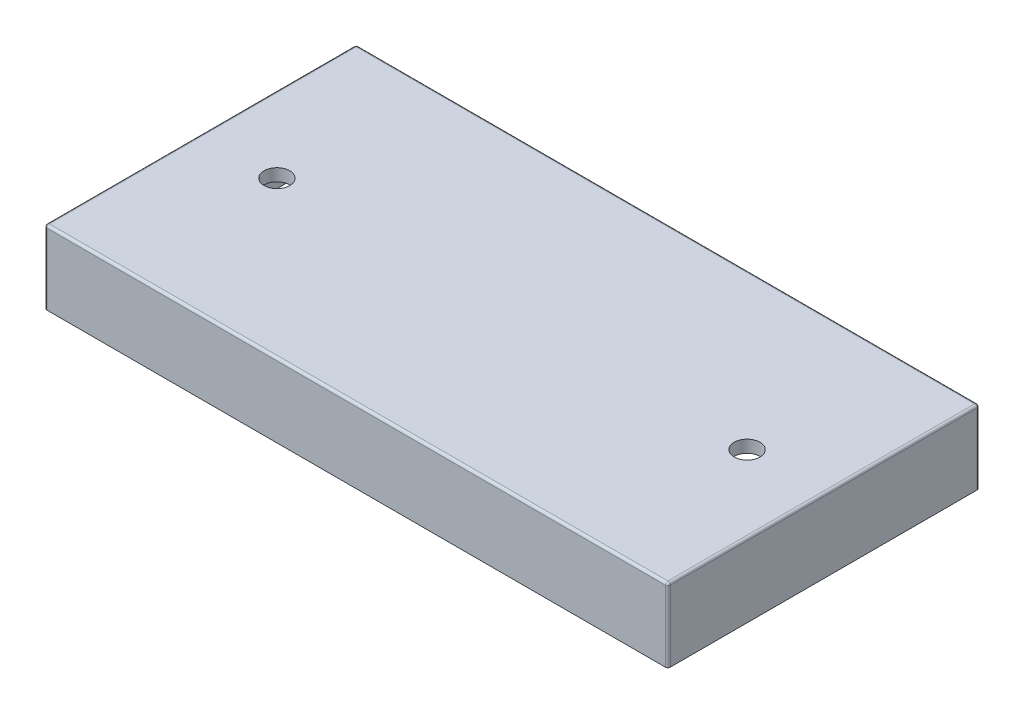
SolidWorks part; units mm, degrees
ref_plane "Front Plane" through (0, 0, 0) normal (0, 0, 1) x (1, 0, 0)
ref_plane "Top Plane" through (0, 0, 0) normal (0, 1, 0) x (1, 0, 0)
ref_plane "Right Plane" through (0, 0, 0) normal (1, 0, 0) x (0, 0, -1)
sketch "Sketch1" plane through (0, 0, 0) normal (0, 1, 0) x (1, 0, 0)
  line L0 (-48.9, 23.45) -> (-48.9, -23.45)
  line L1 (-50.9, 25.45) -> (50.9, 25.45)
  line L2 (-50.9, 25.45) -> (-50.9, -25.45)
  line L3 (-50.9, -25.45) -> (50.9, -25.45)
  line L4 (50.9, 25.45) -> (50.9, -25.45)
  line L5 (-50.9, 25.45) -> (50.9, -25.45) construction
  line L6 (-50.9, -25.45) -> (50.9, 25.45) construction
  line L7 (-48.9, -23.45) -> (48.9, -23.45)
  line L8 (48.9, 23.45) -> (48.9, -23.45)
  line L9 (-48.9, 23.45) -> (48.9, 23.45)
  point P4 (0, 0)
  dimension "D1" = 101.8
  dimension "D2" = 50.9
  dimension "D3" = 2
extrude "Main Body" add sketch "Sketch1" along normal blind 10
sketch "Sketch4" plane through (0, 10, 0) normal (0, 1, 0) x (1, 0, 0)
  line L0 (50.9, 25.45) -> (-50.9, 25.45) construction
  line L1 (-50.9, 25.45) -> (-50.9, -25.45) construction
  line L3 (50.9, -25.45) -> (50.9, 25.45) construction
  line L4 (-50.9, -25.45) -> (50.9, -25.45) construction
  line L5 (50.9, -25.45) -> (50.9, 25.45)
  line L6 (-50.9, -25.45) -> (50.9, -25.45)
  line L7 (-50.9, 25.45) -> (-50.9, -25.45)
  line L8 (50.9, 25.45) -> (-50.9, 25.45)
extrude "Top" add sketch "Sketch4" along normal blind 2
fillet "Outer Fillet 0.2mm" radius 0.4 8 edges at (-50.9, 12, 0) (50.9, 6, -25.45) (50.9, 6, 25.45) (50.9, 12, 0) (0, 12, -25.45) (0, 12, 25.45) (-50.9, 6, 25.45) (-50.9, 6, -25.45)
fillet "Inner Fillet 1mm" radius 1 8 edges at (0, 10, 23.45) (48.9, 10, 0) (0, 10, -23.45) (-48.9, 10, 0) (48.9, 5, 23.45) (-48.9, 5, 23.45) (-48.9, 5, -23.45) (48.9, 5, -23.45)
sketch "Sketch6" plane through (0, 12, 0) normal (0, 1, 0) x (1, 0, 0)
  line L0 (0, 25.05) -> (0, -25.05) construction
  line L5 (50.5, 25.05) -> (-50.5, 25.05) construction
  line L6 (-50.5, -25.05) -> (50.5, -25.05) construction
  line L7 (0, 0) -> (-38.4, 0) construction
  line L8 (-50.5, 25.05) -> (-50.5, -25.05) construction
  line L9 (-40.5, 0) -> (-50.5, 0) construction
  circle A0 centre (-38.4, 0) radius 2.1
  circle A1 centre (38.4, 0) radius 2.1
  dimension "D3" = 4.2
  dimension "D1" = 38.4
  dimension "D4" = 10
extrude "Holes Cut 4.2mm" cut sketch "Sketch6" against normal up to next
